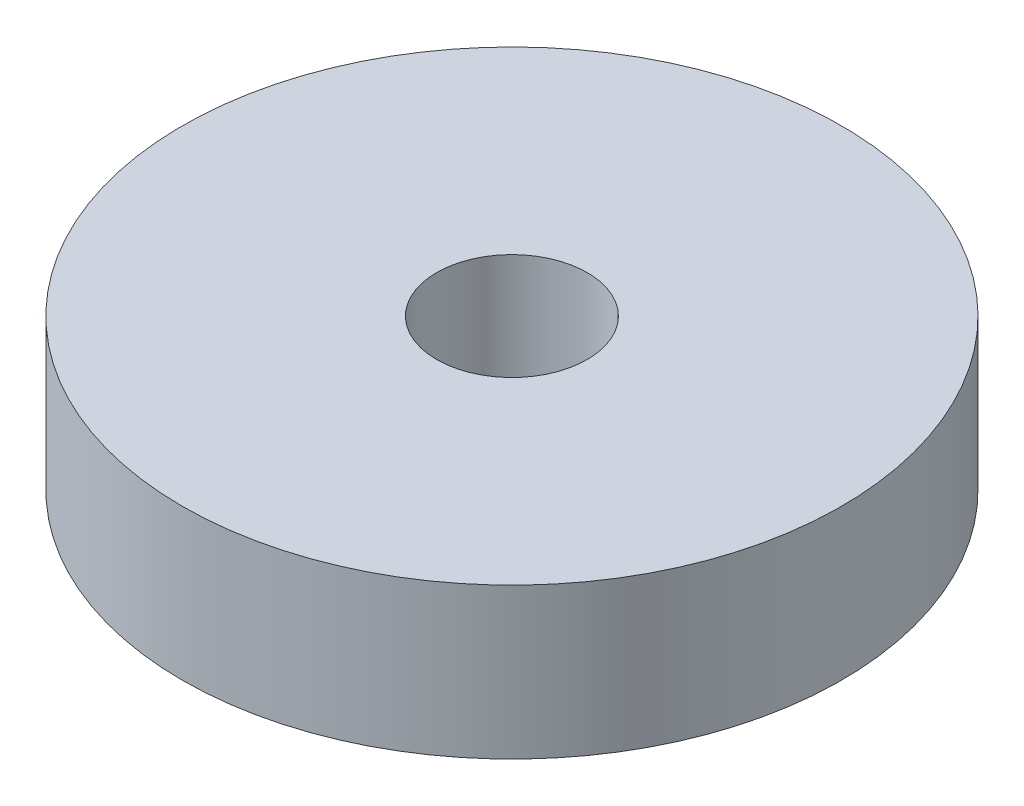
SolidWorks part; units mm, degrees
ref_plane "Front Plane" through (0, 0, 0) normal (0, 0, 1) x (1, 0, 0)
ref_plane "Top Plane" through (0, 0, 0) normal (0, 1, 0) x (1, 0, 0)
ref_plane "Right Plane" through (0, 0, 0) normal (1, 0, 0) x (0, 0, -1)
sketch "Sketch1" plane through (0, 0, 0) normal (0, 1, 0) x (1, 0, 0)
  circle A0 centre (0, 0) radius 4
  circle A1 centre (0, 0) radius 17.5
extrude "Boss-Extrude1" add sketch "Sketch1" along normal blind 8
